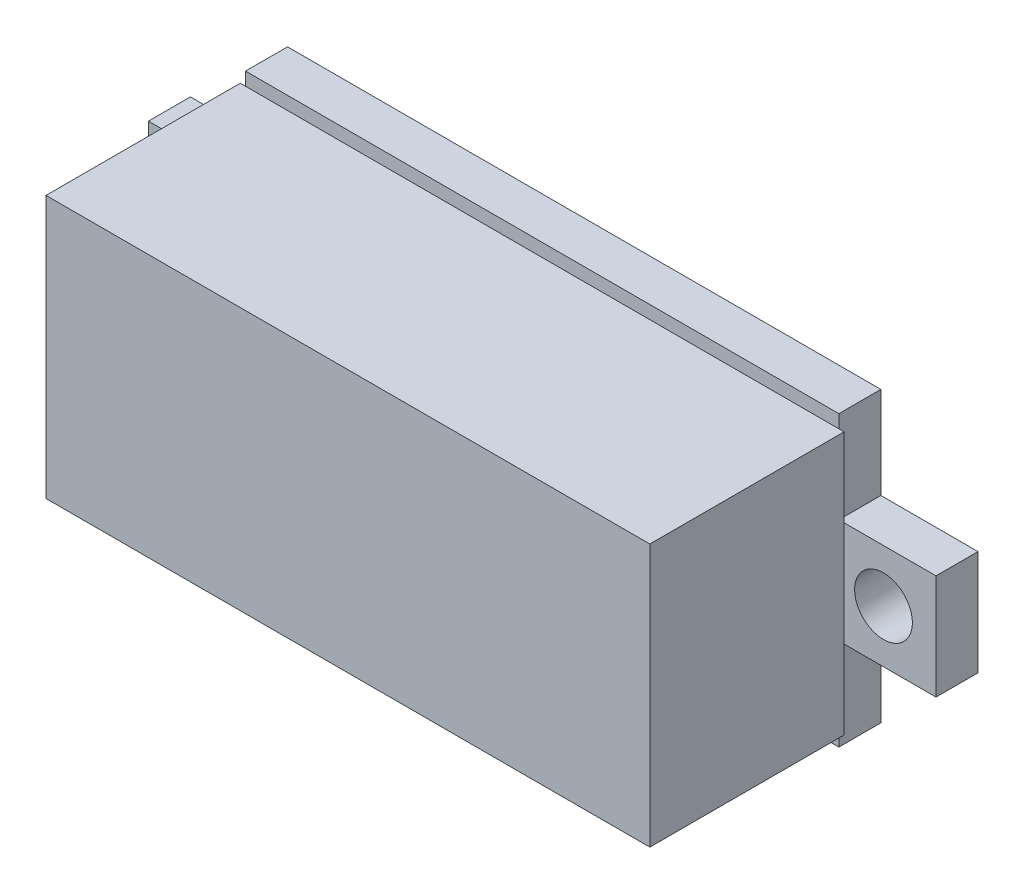
SolidWorks part; units mm, degrees
ref_plane "前视基准面" through (0, 0, 0) normal (0, 0, 1) x (1, 0, 0)
ref_plane "上视基准面" through (0, 0, 0) normal (0, 1, 0) x (1, 0, 0)
ref_plane "右视基准面" through (0, 0, 0) normal (1, 0, 0) x (0, 0, -1)
sketch "草图1" plane through (0, 0, 0) normal (0, 0, 1) x (1, 0, 0)
  line L1 (-11.5, 5) -> (11.5, 5)
  line L2 (-11.5, 5) -> (-11.5, -5)
  line L3 (-11.5, -5) -> (11.5, -5)
  line L4 (11.5, 5) -> (11.5, -5)
  line L5 (-11.5, 5) -> (11.5, -5) construction
  line L6 (-11.5, -5) -> (11.5, 5) construction
  point P0 (0, 0)
  dimension "D1" = 23
  dimension "D2" = 10
extrude "凸台-拉伸1" add sketch "草图1" along normal blind 7.4
sketch "草图2" plane through (0, 0, 0) normal (0, 0, -1) x (-1, 0, 0)
  line L0 (-11.3, -2) -> (-11.3, -5.5)
  line L1 (-11.3, 5.5) -> (11.3, 5.5)
  line L2 (-11.3, 5.5) -> (-11.3, 2)
  line L3 (-11.3, -5.5) -> (11.3, -5.5)
  line L4 (11.3, 5.5) -> (11.3, 2)
  line L5 (13, 0) -> (-13, 0) construction
  line L6 (-11.3, -2) -> (-15, -2)
  line L7 (15, -2) -> (11.3, -2)
  line L8 (15, -2) -> (15, 2)
  line L9 (15, 2) -> (11.3, 2)
  line L10 (-15, -2) -> (-15, 2)
  line L11 (11.3, -2) -> (11.3, -5.5)
  line L12 (-11.3, 2) -> (-15, 2)
  circle A0 centre (-13, 0) radius 1.1
  circle A1 centre (13, 0) radius 1.1
  point P0 (0, 0)
  point P6 (0, 0)
  point P18 (0, 0)
  dimension "D6" = 2.2
  dimension "D7" = 2.2
  dimension "D1" = 11
  dimension "D2" = 22.6
  dimension "D3" = 4
  dimension "D4" = 30
  dimension "D5" = 26
extrude "凸台-拉伸2" add sketch "草图2" along normal blind 1.6
